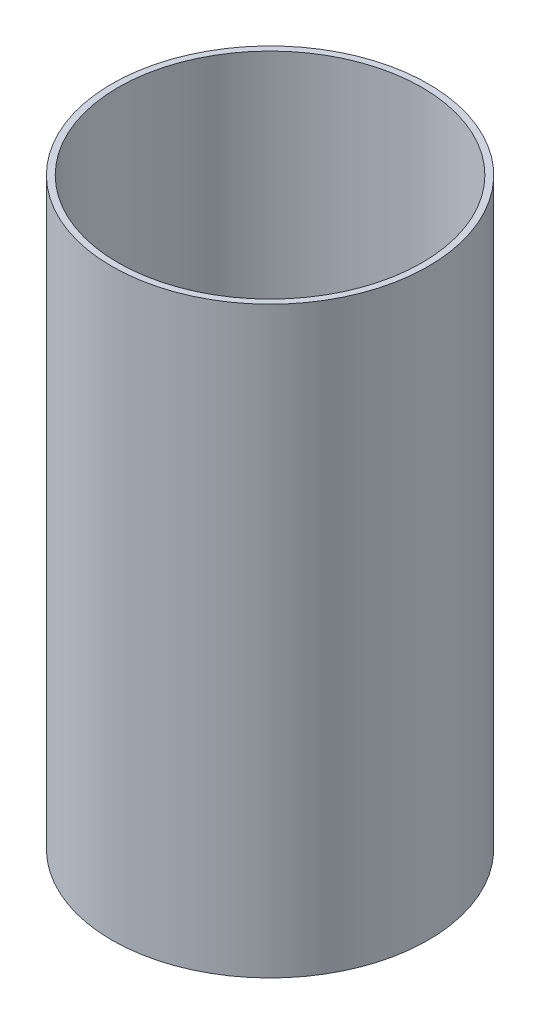
SolidWorks part; units mm, degrees
ref_plane "Front Plane" through (0, 0, 0) normal (0, 0, 1) x (1, 0, 0)
ref_plane "Top Plane" through (0, 0, 0) normal (0, 1, 0) x (1, 0, 0)
ref_plane "Right Plane" through (0, 0, 0) normal (1, 0, 0) x (0, 0, -1)
sketch "Sketch1" plane through (0, 0, 0) normal (0, 1, 0) x (1, 0, 0)
  circle A0 centre (0, 0) radius 36.45
  circle A1 centre (0, 0) radius 37.95
  dimension "D1" = 72.9
  dimension "D2" = 1.5
extrude "Boss-Extrude1" add sketch "Sketch1" along normal blind 140
